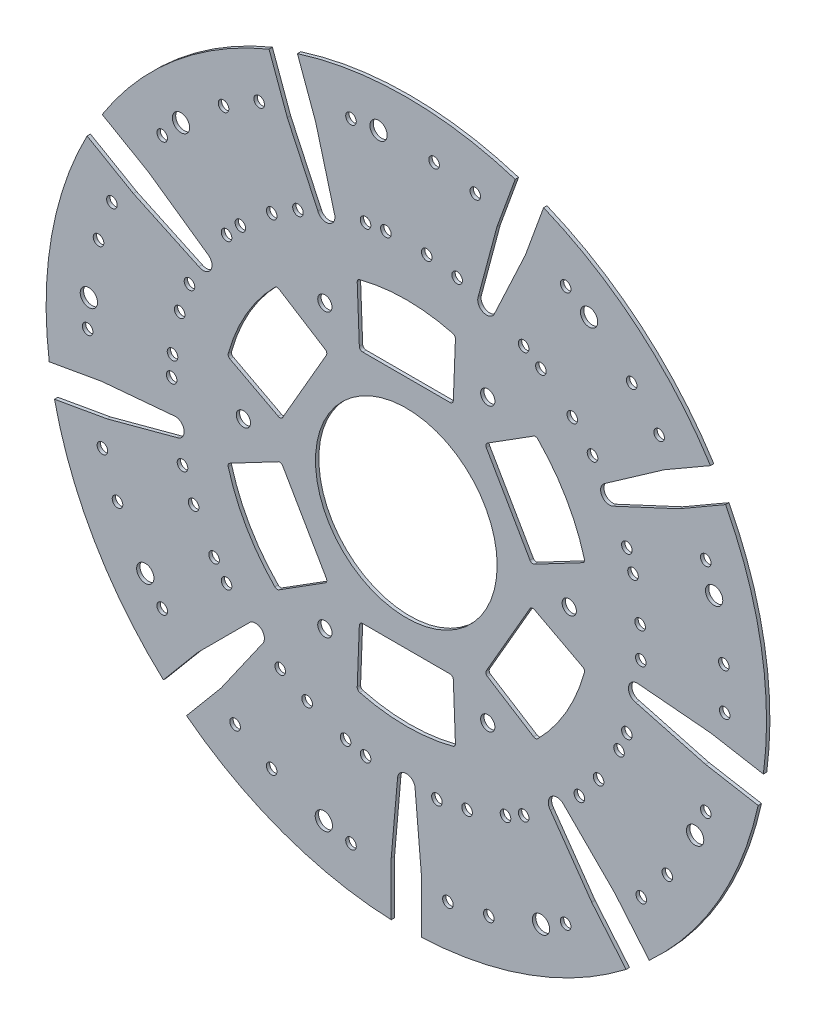
SolidWorks part; units mm, degrees
ref_plane "Plano frontal" through (0, 0, 0) normal (0, 0, 1) x (1, 0, 0)
ref_plane "Plano superior" through (0, 0, 0) normal (0, 1, 0) x (1, 0, 0)
ref_plane "Plano direito" through (0, 0, 0) normal (1, 0, 0) x (0, 0, -1)
sketch "Esboço1" plane through (0, 0, 0) normal (0, 0, 1) x (1, 0, 0)
  circle A0 centre (0, 0) radius 214.5
  circle A1 centre (0, 0) radius 54.1
  dimension "D1" = 429
  dimension "D2" = 108.2
extrude "Ressalto-extrusão1" add sketch "Esboço1" along normal blind 2
sketch "Esboço2" plane through (0, 0, 2) normal (0, 0, 1) x (1, 0, 0)
  line L1 (0, 214.5) -> (0, 0) construction
  line L4 (64.9061, 204.6422) -> (53.9614, 174.5721)
  line L7 (64.9061, 204.6422) -> (81.8206, 198.4859)
  line L8 (81.8206, 198.4859) -> (70.8759, 168.4157)
  line L9 (53.9614, 174.5721) -> (42.829, 133.0253)
  line L10 (70.8759, 168.4157) -> (52.6981, 129.4333)
  line L16 (181.2624, 115.0442) -> (153.5496, 99.0442)
  line L17 (181.2624, 115.0442) -> (190.2624, 99.4558)
  line L18 (190.2624, 99.4558) -> (162.5496, 83.4558)
  line L19 (153.5496, 99.0442) -> (118.316, 74.3733)
  line L20 (162.5496, 83.4558) -> (123.5672, 65.278)
  line L26 (212.8041, -28.3843) -> (181.2902, -22.8275)
  line L27 (212.8041, -28.3843) -> (209.6784, -46.1108)
  line L28 (209.6784, -46.1108) -> (178.1646, -40.5541)
  line L29 (181.2902, -22.8275) -> (138.4416, -19.0787)
  line L30 (178.1646, -40.5541) -> (136.6178, -29.4216)
  line L36 (144.7723, -158.5314) -> (124.2031, -134.018)
  line L37 (144.7723, -158.5314) -> (130.9835, -170.1016)
  line L38 (130.9835, -170.1016) -> (110.4143, -145.5882)
  line L39 (124.2031, -134.018) -> (93.7888, -103.6037)
  line L40 (110.4143, -145.5882) -> (85.7435, -110.3545)
  line L46 (9, -214.5) -> (9, -182.5)
  line L47 (9, -214.5) -> (-9, -214.5)
  line L48 (-9, -214.5) -> (-9, -182.5)
  line L49 (9, -182.5) -> (5.2512, -139.6513)
  line L50 (-9, -182.5) -> (-5.2512, -139.6513)
  line L56 (-130.9835, -170.1016) -> (-110.4143, -145.5882)
  line L57 (-130.9835, -170.1016) -> (-144.7723, -158.5314)
  line L58 (-144.7723, -158.5314) -> (-124.2031, -134.018)
  line L59 (-110.4143, -145.5882) -> (-85.7435, -110.3545)
  line L60 (-124.2031, -134.018) -> (-93.7888, -103.6037)
  line L66 (-209.6784, -46.1108) -> (-178.1646, -40.5541)
  line L67 (-209.6784, -46.1108) -> (-212.8041, -28.3843)
  line L68 (-212.8041, -28.3843) -> (-181.2902, -22.8275)
  line L69 (-178.1646, -40.5541) -> (-136.6178, -29.4216)
  line L70 (-181.2902, -22.8275) -> (-138.4416, -19.0787)
  line L76 (-190.2624, 99.4558) -> (-162.5496, 83.4558)
  line L77 (-190.2624, 99.4558) -> (-181.2624, 115.0442)
  line L78 (-181.2624, 115.0442) -> (-153.5496, 99.0442)
  line L79 (-162.5496, 83.4558) -> (-123.5672, 65.278)
  line L80 (-153.5496, 99.0442) -> (-118.316, 74.3733)
  line L86 (-81.8206, 198.4859) -> (-70.8759, 168.4157)
  line L87 (-81.8206, 198.4859) -> (-64.9061, 204.6422)
  line L88 (-64.9061, 204.6422) -> (-53.9614, 174.5721)
  line L89 (-70.8759, 168.4157) -> (-52.6981, 129.4333)
  line L90 (-53.9614, 174.5721) -> (-42.829, 133.0253)
  circle A0 centre (0, 0) radius 214.5 construction
  arc A3 (42.829, 133.0253) -> (52.6981, 129.4333) centre (47.7636, 131.2293) ccw
  arc A5 (118.316, 74.3733) -> (123.5672, 65.278) centre (120.9416, 69.8257) ccw
  arc A7 (138.4416, -19.0787) -> (136.6178, -29.4216) centre (137.5297, -24.2502) ccw
  arc A9 (93.7888, -103.6037) -> (85.7435, -110.3545) centre (89.7661, -106.9791) ccw
  arc A11 (5.2512, -139.6513) -> (-5.2512, -139.6513) centre (0, -139.6513) ccw
  arc A13 (-85.7435, -110.3545) -> (-93.7888, -103.6037) centre (-89.7661, -106.9791) ccw
  arc A15 (-136.6178, -29.4216) -> (-138.4416, -19.0787) centre (-137.5297, -24.2502) ccw
  arc A17 (-123.5672, 65.278) -> (-118.316, 74.3733) centre (-120.9416, 69.8257) ccw
  arc A19 (-52.6981, 129.4333) -> (-42.829, 133.0253) centre (-47.7636, 131.2293) ccw
  point P134 (0, 0)
extrude "Corte-extrusão1" cut sketch "Esboço2" against normal blind 2
sketch "Esboço3" plane through (0, 0, 2) normal (0, 0, 1) x (1, 0, 0)
  line L0 (0, 0) -> (0, 189.75) construction
  line L1 (0, 0) -> (-16.5378, 189.0279) construction
  line L2 (0, 0) -> (-32.9497, 186.8673) construction
  line L3 (0, 0) -> (16.5378, 189.0279) construction
  line L4 (0, 0) -> (41.0694, 185.2522) construction
  circle A0 centre (0, 0) radius 189.75 construction
  circle A1 centre (0, 0) radius 139.75 construction
  circle A2 centre (-32.9497, 186.8673) radius 3.15
  circle A3 centre (-16.5378, 189.0279) radius 5.15
  circle A4 centre (16.5378, 189.0279) radius 3.15
  circle A5 centre (41.0694, 185.2522) radius 3.15
  circle A6 centre (30.2474, 136.4374) radius 3.15
  circle A7 centre (12.18, 139.2182) radius 3.15
  circle A8 centre (-12.18, 139.2182) radius 3.15
  circle A9 centre (-24.2673, 137.6269) radius 3.15
  circle A10 centre (94.875, 164.3283) radius 3.15
  circle A11 centre (108.8361, 155.4341) radius 5.15
  circle A12 centre (134.1735, 134.1735) radius 3.15
  circle A13 centre (150.5388, 115.5125) radius 3.15
  circle A14 centre (110.8711, 85.0744) radius 3.15
  circle A15 centre (98.8182, 98.8182) radius 3.15
  circle A16 centre (80.1573, 114.4765) radius 3.15
  circle A17 centre (69.875, 121.0271) radius 3.15
  circle A18 centre (178.3067, 64.8983) radius 3.15
  circle A19 centre (183.2844, 49.1109) radius 5.15
  circle A20 centre (189.0279, 16.5378) radius 3.15
  circle A21 centre (189.5694, -8.2768) radius 3.15
  circle A22 centre (139.617, -6.0958) radius 3.15
  circle A23 centre (139.2182, 12.18) radius 3.15
  circle A24 centre (134.9881, 36.17) radius 3.15
  circle A25 centre (131.322, 47.7973) radius 3.15
  circle A26 centre (178.3067, -64.8983) radius 3.15
  circle A27 centre (171.9719, -80.1918) radius 5.15
  circle A28 centre (155.4341, -108.8361) radius 3.15
  circle A29 centre (139.8984, -128.1932) radius 3.15
  circle A30 centre (103.0345, -94.4137) radius 3.15
  circle A31 centre (114.4765, -80.1573) radius 3.15
  circle A32 centre (126.6565, -59.0609) radius 3.15
  circle A33 centre (131.322, -47.7973) radius 3.15
  circle A34 centre (94.875, -164.3283) radius 3.15
  circle A35 centre (80.1918, -171.9719) radius 5.15
  circle A36 centre (49.1109, -183.2844) radius 3.15
  circle A37 centre (24.7673, -188.1267) radius 3.15
  circle A38 centre (18.241, -138.5544) radius 3.15
  circle A39 centre (36.17, -134.9881) radius 3.15
  circle A40 centre (59.0609, -126.6565) radius 3.15
  circle A41 centre (69.875, -121.0271) radius 3.15
  circle A42 centre (-32.9497, -186.8673) radius 3.15
  circle A43 centre (-49.1109, -183.2844) radius 5.15
  circle A44 centre (-80.1918, -171.9719) radius 3.15
  circle A45 centre (-101.9526, -160.0335) radius 3.15
  circle A46 centre (-75.0876, -117.864) radius 3.15
  circle A47 centre (-59.0609, -126.6565) radius 3.15
  circle A48 centre (-36.17, -134.9881) radius 3.15
  circle A49 centre (-24.2673, -137.6269) radius 3.15
  circle A50 centre (-145.3569, -121.9689) radius 3.15
  circle A51 centre (-155.4341, -108.8361) radius 5.15
  circle A52 centre (-171.9719, -80.1918) radius 3.15
  circle A53 centre (-180.9678, -57.0589) radius 3.15
  circle A54 centre (-133.2819, -42.0236) radius 3.15
  circle A55 centre (-126.6565, -59.0609) radius 3.15
  circle A56 centre (-114.4765, -80.1573) radius 3.15
  circle A57 centre (-107.0547, -89.8296) radius 3.15
  circle A58 centre (-189.75, 0) radius 3.15
  circle A59 centre (-189.0279, 16.5378) radius 5.15
  circle A60 centre (-183.2844, 49.1109) radius 3.15
  circle A61 centre (-175.3061, 72.6142) radius 3.15
  circle A62 centre (-129.1122, 53.48) radius 3.15
  circle A63 centre (-134.9881, 36.17) radius 3.15
  circle A64 centre (-139.2182, 12.18) radius 3.15
  circle A65 centre (-139.75, 0) radius 3.15
  circle A66 centre (-145.3569, 121.9689) radius 3.15
  circle A67 centre (-134.1735, 134.1735) radius 5.15
  circle A68 centre (-108.8361, 155.4341) radius 3.15
  circle A69 centre (-87.6168, 168.3103) radius 3.15
  circle A70 centre (-64.5294, 123.9598) radius 3.15
  circle A71 centre (-80.1573, 114.4765) radius 3.15
  circle A72 centre (-98.8182, 98.8182) radius 3.15
  circle A73 centre (-107.0547, 89.8296) radius 3.15
  point P152 (0, 0)
  dimension "D1" = 379.5
  dimension "D2" = 279.5
  dimension "D7" = 6.3
  dimension "D8" = 10.3
  dimension "D9" = 6.3
  dimension "D3" = 5
  dimension "D4" = 5
  dimension "D5" = 5
  dimension "D6" = 7.5
extrude "Corte-extrusão2" cut sketch "Esboço3" against normal blind 2
sketch "Esboço4" plane through (0, 0, 2) normal (0, 0, 1) x (1, 0, 0)
  line L1 (-27.91, 70) -> (27.91, 70)
  line L3 (46.6668, 59.1708) -> (74.5768, 10.8292)
  line L4 (46.6668, 59.1708) -> (77.1675, 78.3912)
  line L5 (-27.91, 70) -> (-29.305, 106.0246)
  line L6 (29.305, 106.0246) -> (27.91, 70)
  line L7 (106.4725, 27.6334) -> (74.5768, 10.8292)
  line L9 (74.5768, -10.8292) -> (46.6668, -59.1708)
  line L10 (74.5768, -10.8292) -> (106.4725, -27.6334)
  line L11 (77.1675, -78.3912) -> (46.6668, -59.1708)
  line L13 (27.91, -70) -> (-27.91, -70)
  line L14 (27.91, -70) -> (29.305, -106.0246)
  line L15 (-29.305, -106.0246) -> (-27.91, -70)
  line L17 (-46.6668, -59.1708) -> (-74.5768, -10.8292)
  line L18 (-46.6668, -59.1708) -> (-77.1675, -78.3912)
  line L19 (-106.4725, -27.6334) -> (-74.5768, -10.8292)
  line L21 (-74.5768, 10.8292) -> (-46.6668, 59.1708)
  line L22 (-74.5768, 10.8292) -> (-106.4725, 27.6334)
  line L23 (-77.1675, 78.3912) -> (-46.6668, 59.1708)
  arc A0 (-29.305, 106.0246) -> (29.305, 106.0246) centre (0, 0) cw
  arc A1 (77.1675, 78.3912) -> (106.4725, 27.6334) centre (0, 0) cw
  arc A2 (106.4725, -27.6334) -> (77.1675, -78.3912) centre (0, 0) cw
  arc A3 (29.305, -106.0246) -> (-29.305, -106.0246) centre (0, 0) cw
  arc A4 (-77.1675, -78.3912) -> (-106.4725, -27.6334) centre (0, 0) cw
  arc A5 (-106.4725, 27.6334) -> (-77.1675, 78.3912) centre (0, 0) cw
  point P40 (0, 0)
  dimension "D1" = 6
extrude "Corte-extrusão3" cut sketch "Esboço4" against normal blind 2
sketch "Esboço5" plane through (0, 0, 2) normal (0, 0, 1) x (1, 0, 0)
  circle A2 centre (48.5, 84.0045) radius 4.25
  circle A4 centre (97, 0) radius 4.25
  circle A6 centre (48.5, -84.0045) radius 4.25
  circle A8 centre (-48.5, -84.0045) radius 4.25
  circle A10 centre (-97, 0) radius 4.25
  circle A12 centre (-48.5, 84.0045) radius 4.25
  point P29 (0, 0)
extrude "Corte-extrusão4" cut sketch "Esboço5" against normal blind 2
fillet "Filete1" radius 2 24 edges at (-46.6668, -59.1708, 1) (-77.1675, -78.3912, 1) (-106.4725, -27.6334, 1) (-74.5768, -10.8292, 1) (29.305, -106.0246, 1) (-29.305, -106.0246, 1) (-27.91, -70, 1) (27.91, -70, 1) (77.1675, -78.3912, 1) (46.6668, -59.1708, 1) (74.5768, -10.8292, 1) (106.4725, -27.6334, 1) (74.5768, 10.8292, 1) (106.4725, 27.6334, 1) (46.6668, 59.1708, 1) (77.1675, 78.3912, 1) (-46.6668, 59.1708, 1) (-74.5768, 10.8292, 1) (-106.4725, 27.6334, 1) (-77.1675, 78.3912, 1) (27.91, 70, 1) (-27.91, 70, 1) (-29.305, 106.0246, 1) (29.305, 106.0246, 1)
